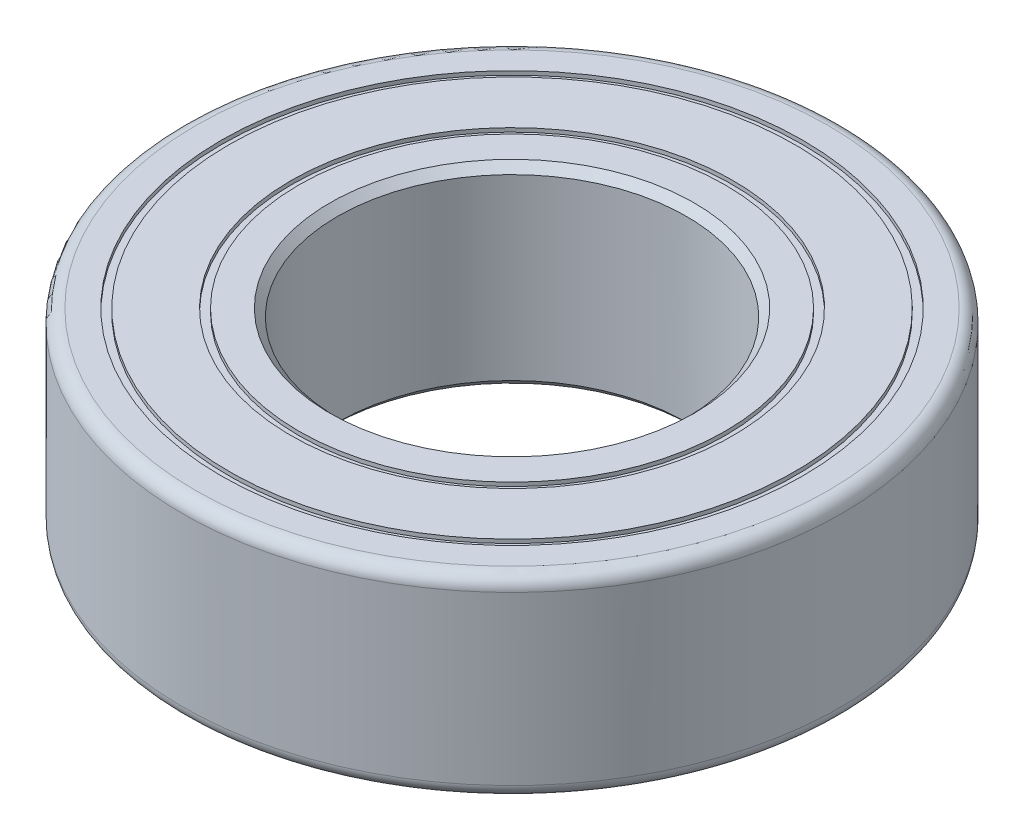
SolidWorks part; units mm, degrees
ref_plane "Front Plane" through (0, 0, 0) normal (0, 0, 1) x (1, 0, 0)
ref_plane "Top Plane" through (0, 0, 0) normal (0, 1, 0) x (1, 0, 0)
ref_plane "Right Plane" through (0, 0, 0) normal (1, 0, 0) x (0, 0, -1)
sketch "Sketch1" plane through (0, 0, 0) normal (0, 0, 1) x (1, 0, 0)
  line L0 (0, 0) -> (4.5, 0) construction
  line L1 (8.5, 0) -> (8.5, 5)
  line L3 (0, 2.5) -> (0, 0) construction
  line L4 (4.5, 0) -> (4.5, 5)
  line L5 (4.5, 0) -> (5.5, 0)
  line L6 (5.5, 0) -> (5.5, 0.1)
  line L7 (5.5, 0.1) -> (5.7, 0.1)
  line L8 (5.7, 0.1) -> (5.7, 0)
  line L9 (5.7, 0) -> (7.3, 0)
  line L10 (6.5, 0) -> (6.5, 2.5) construction
  line L11 (8.5, 2.5) -> (4.5, 2.5) construction
  line L12 (4.5, 2.5) -> (0, 2.5) construction
  line L13 (7.3, 0.1) -> (7.3, 0)
  line L14 (7.5, 0.1) -> (7.3, 0.1)
  line L15 (7.5, 0) -> (7.5, 0.1)
  line L16 (8.5, 0) -> (7.5, 0)
  line L17 (8.5, 5) -> (7.5, 5)
  line L18 (7.5, 5) -> (7.5, 4.9)
  line L19 (7.5, 4.9) -> (7.3, 4.9)
  line L20 (7.3, 4.9) -> (7.3, 5)
  line L21 (5.7, 5) -> (7.3, 5)
  line L22 (5.7, 4.9) -> (5.7, 5)
  line L23 (5.5, 4.9) -> (5.7, 4.9)
  line L24 (5.5, 5) -> (5.5, 4.9)
  line L25 (4.5, 5) -> (5.5, 5)
  dimension "D1" = 8.5
  dimension "D2" = 4.5
  dimension "D4" = 1
  dimension "D5" = 0.2
  dimension "D6" = 0.1
  dimension "D3" = 5
revolve "Revolve1" add sketch "Sketch1" angle 360 about L3
fillet "Fillet2" radius 0.344 2 edges at (-8.5, 0, 0) (-8.5, 5, 0)
chamfer "Chamfer2" distance 0.2 angle 45 2 edges at (-4.5, 0, 0) (-4.5, 5, 0)
equation "\"Ratio\"= 15"
equation "\"Hull Diameter\"= 92"
equation "\"Fixed Ring Diameter\"= 76"
equation "\"Fixed Pin Diameter\"= 6"
equation "\"Output Ring Diameter\"= 40"
equation "\"Output Pin Diameter\"= 6"
equation "\"Disk Bearing Inner Diameter\"= 9"
equation "\"Disk Bearing Outer Diameter\"= 17"
equation "\"Disk Bearing Height\"= 5"
equation "\"Shaft Bearing Inner Diameter\"= 15"
equation "\"Shaft Bearing Outer Diameter\"= 21"
equation "\"Shaft Bearing Height\"= 4"
equation "\"Eccentricity\"= 1.5"
equation "\"Disk Height\"= 8"
equation "\"Disk Spacing\"= 5"
equation "\"Hull Height\"= 40"
equation "\"Shaft End Bearing Inner Diameter\"= 12"
equation "\"Shaft End Bearing Outer Diameter\"= 18"
equation "\"Shaft End Bearing Height\"= 4"
equation "\"Output Bearing Inner Diameter\"= 55"
equation "\"Output Bearing Outer Diameter\"= 72"
equation "\"Outer Bearing Height\"= 9"
equation "\"D3@Sketch1\"= \"Disk Bearing Height\""
equation "\"D2@Sketch1\" = \"Disk Bearing Inner Diameter\" / 2"
equation "\"D1@Sketch1\" = \"Disk Bearing Outer Diameter\" / 2"
